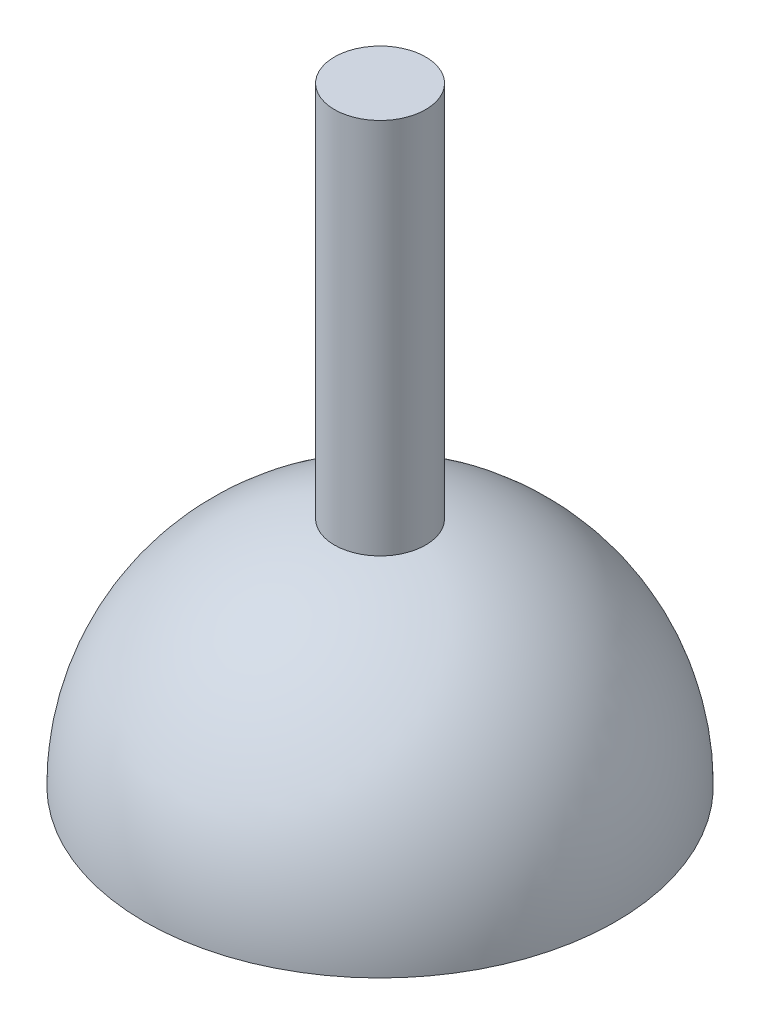
SolidWorks part; units mm, degrees
ref_plane "Front Plane" through (0, 0, 0) normal (0, 0, 1) x (1, 0, 0)
ref_plane "Top Plane" through (0, 0, 0) normal (0, 1, 0) x (1, 0, 0)
ref_plane "Right Plane" through (0, 0, 0) normal (1, 0, 0) x (0, 0, -1)
other "Center of Mass"
sketch "Sketch2" plane through (0, 0, 0) normal (0, 1, 0) x (1, 0, 0)
  line L0 (0, -40.1532) -> (0, 40.1532) construction
  arc A0 (0, -30) -> (0, 30) centre (0, 0) ccw
  point P6 (0, 0)
  dimension "D1" = 60
revolve "Revolve-Thin1" add sketch "Sketch2" angle 360 about L0
ref_plane "Plane2" through (0, 0, 0) normal (0, 1, 0) x (1, 0, 0)
sketch "Sketch4" plane through (0, 0, 0) normal (0, 1, 0) x (1, 0, 0)
  circle A0 centre (0, 0) radius 31
extrude "Cut-Extrude1" cut sketch "Sketch4" against normal blind 50
sketch "Sketch5" plane through (0, 0, 0) normal (0, 1, 0) x (1, 0, 0)
  line L0 (31, 0) -> (-31, 0) construction
  line L1 (0, -31) -> (0, 31) construction
  circle A0 centre (0, 0) radius 31 construction
  point P0 (0, 0)
  point P7 (0, 0)
  point P11 (0, 0)
ref_plane "Plane3" through (0, 30, 0) normal (0, 1, 0) x (1, 0, 0)
sketch "Sketch6" plane through (0, 30, 0) normal (0, 1, 0) x (1, 0, 0)
  circle A0 centre (0, 0) radius 6
  dimension "D1" = 12
extrude "Boss-Extrude1" add sketch "Sketch6" along normal blind 50 separate body
